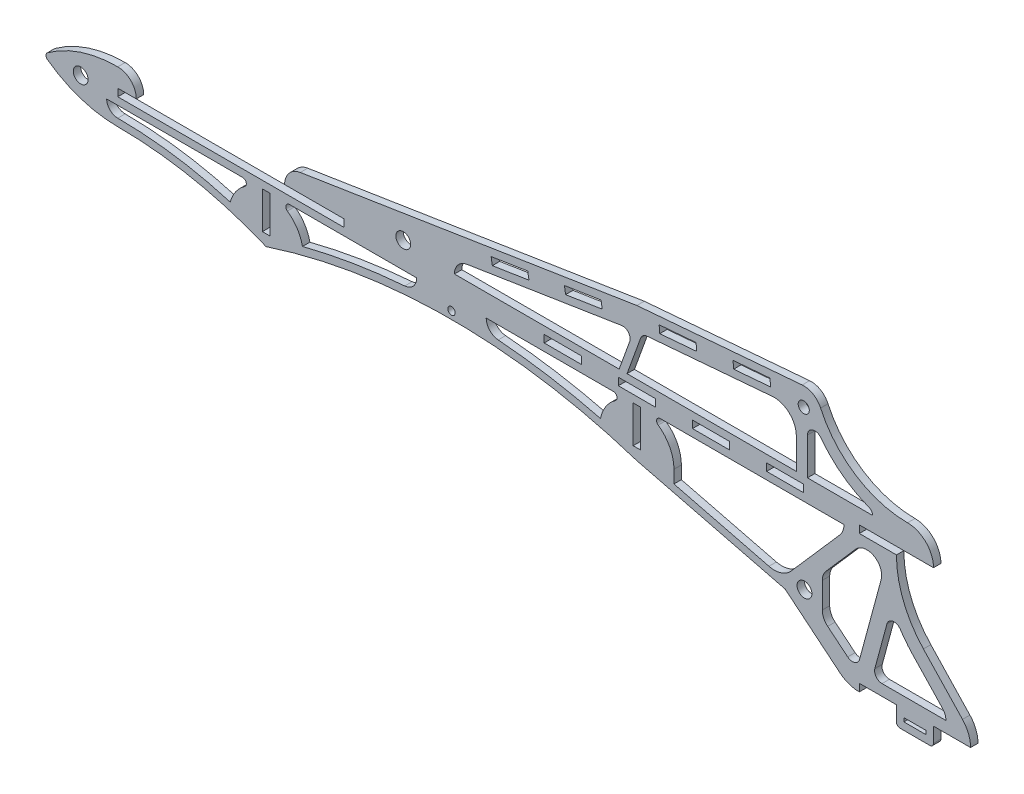
SolidWorks part; units mm, degrees
ref_plane "Front Plane" through (0, 0, 0) normal (0, 0, 1) x (1, 0, 0)
ref_plane "Top Plane" through (0, 0, 0) normal (0, 1, 0) x (1, 0, 0)
ref_plane "Right Plane" through (0, 0, 0) normal (1, 0, 0) x (0, 0, -1)
sketch "Sketch1" plane through (0, 0, 0) normal (0, 0, 1) x (1, 0, 0)
  line L0 (25, 2) -> (20, 2)
  line L1 (-10, 0) -> (249.25, 0) construction
  line L2 (20, 2) -> (20, 0)
  line L3 (20, 0) -> (81, 0)
  line L4 (65, 2) -> (81, 2)
  line L5 (81, 2) -> (81, 0)
  line L6 (66.3246, -2) -> (100.6353, -2)
  line L7 (59, -12) -> (59, -2)
  line L8 (61, -12) -> (59, -12)
  line L9 (59, -2) -> (61, -2)
  line L10 (17, -2) -> (53.6754, -2)
  line L11 (160, 21.25) -> (69.2214, 6.939)
  line L12 (160, 21.25) -> (204.5828, 24.9826)
  line L13 (160, -15) -> (200, -25)
  line L14 (200, -25) -> (214.7845, -37.1754)
  line L15 (219.8701, -39) -> (220, -39)
  line L16 (220, -39) -> (220, -37)
  line L17 (220, -37) -> (230, -37)
  line L18 (230, -37) -> (230, -41)
  line L19 (231, -42) -> (239, -42)
  line L20 (240, -41) -> (240, -37)
  line L21 (240, -37) -> (250, -37)
  line L22 (237.2765, -20.3267) -> (247.8212, -31.5124)
  line L23 (232, -39) -> (238, -39)
  line L24 (232, -39) -> (232, -40)
  line L25 (232, -40) -> (238, -40)
  line L26 (238, -39) -> (238, -40)
  line L27 (230, -2) -> (220, -2)
  line L29 (220, 0) -> (240, 0)
  line L30 (61, -2) -> (61, -12)
  line L31 (159, -12) -> (161, -12)
  line L32 (159, -12) -> (159, -2)
  line L33 (159, -2) -> (161, -2)
  line L34 (161, -12) -> (161, -2)
  line L35 (170, -15.4384) -> (195.6265, -21.8451)
  line L36 (119.3647, -2) -> (153.6754, -2)
  line L37 (166.3246, -2) -> (215.8581, -2)
  line L38 (170, -12) -> (170, -15.4384)
  line L39 (160.5551, -13.0772) -> (200.4851, -23.0597) construction
  line L40 (225.88, -9.8441) -> (220.0588, -31.3826)
  line L41 (155.22, 4) -> (158.0674, 11.8696)
  line L42 (162.7314, 15.4577) -> (196.4994, 18.2848)
  line L43 (155.8752, 14.5256) -> (114.1717, 7.9512)
  line L44 (157.3469, 4) -> (161.0176, 14.1451)
  line L45 (110.7946, 4) -> (155.22, 4)
  line L46 (160.7184, 15.2892) -> (70.1557, 1.0122) construction
  line L47 (157.1007, 3.3195) -> (161.0998, 14.3723) construction
  line L48 (157.3469, 4) -> (203, 4)
  line L49 (160.7184, 15.2892) -> (205.0834, 19.0035) construction
  line L50 (155.22, 4) -> (159.2191, 15.0528) construction
  line L51 (203, 12.3057) -> (203, 4)
  line L52 (206, 13.9815) -> (206, 4)
  line L53 (206, 4) -> (223.5862, 4)
  line L54 (166, 19.7453) -> (175.9651, 20.5796)
  line L55 (150.334, 17.7015) -> (140.456, 16.1442)
  line L56 (166.1669, 17.7523) -> (176.132, 18.5866)
  line L57 (150.6455, 15.7259) -> (140.7675, 14.1686)
  line L58 (121.0114, 11.0542) -> (120.7, 13.0298)
  line L59 (130.8895, 12.6114) -> (130.578, 14.587)
  line L60 (160.2395, 19.2631) -> (69.5328, 4.9634) construction
  line L61 (160.4789, 17.2761) -> (69.8443, 2.9878) construction
  line L62 (140.7675, 14.1686) -> (140.456, 16.1442)
  line L63 (150.6455, 15.7259) -> (150.334, 17.7015)
  line L64 (130.578, 14.587) -> (120.7, 13.0298)
  line L65 (130.8895, 12.6114) -> (121.0114, 11.0542)
  line L66 (166.1669, 17.7523) -> (166, 19.7453)
  line L67 (176.132, 18.5866) -> (175.9651, 20.5796)
  line L68 (160.4789, 17.2761) -> (204.9166, 20.9965) construction
  line L69 (160.2395, 19.2631) -> (204.7497, 22.9895) construction
  line L70 (186.0971, 19.4209) -> (185.9303, 21.4139)
  line L71 (196.0623, 20.2552) -> (195.8954, 22.2482)
  line L72 (185.9303, 21.4139) -> (195.8954, 22.2482)
  line L73 (186.0971, 19.4209) -> (196.0623, 20.2552)
  line L74 (220, -2) -> (220, 0)
  line L75 (227.4331, -19.4284) -> (224.1764, -31.4782)
  line L76 (234.3659, -23.0705) -> (242.4058, -31.5992)
  line L77 (231.8615, -3.0436) -> (221.9178, -39.8353) construction
  line L78 (226.1072, -34) -> (243.3591, -34)
  line L79 (228, -2) -> (218.0563, -38.7917) construction
  line L80 (210.9909, -15.3206) -> (219.0094, -6.165)
  line L81 (234.3659, -23.0705) -> (244.9106, -34.2562) construction
  line L82 (201.5953, -19.9773) -> (214.7434, -4.9648)
  line L83 (210, -17.956) -> (210, -24.8703)
  line L84 (202.1903, -25.3691) -> (220.3491, -4.6354) construction
  line L85 (199.1812, -22.7337) -> (217.34, -2) construction
  line L86 (211.4572, -27.958) -> (216.8566, -32.4046)
  line L87 (135, 0) -> (145, 0)
  line L88 (135, 0) -> (135, 2)
  line L89 (135, 2) -> (145, 2)
  line L90 (145, 0) -> (145, 2)
  line L91 (155, 0) -> (165, 0)
  line L92 (155, 0) -> (155, 2)
  line L93 (155, 2) -> (165, 2)
  line L94 (165, 0) -> (165, 2)
  line L95 (175, 0) -> (185, 0)
  line L96 (175, 0) -> (175, 2)
  line L97 (175, 2) -> (185, 2)
  line L98 (185, 0) -> (185, 2)
  line L99 (195, 0) -> (205, 0)
  line L100 (195, 0) -> (195, 2)
  line L101 (195, 2) -> (205, 2)
  line L102 (205, 0) -> (205, 2)
  arc A0 (1.0556, 0.8069) -> (20, 7) centre (20, -25.0714) cw
  arc A1 (1.0556, -0.8069) -> (20, -7) centre (20, 25.0714) ccw
  arc A2 (25, 2) -> (20, 7) centre (20, 2) ccw
  arc A3 (20, -7) -> (60, -15) centre (20, -111) cw
  circle A4 centre (10, 0) radius 2
  arc A5 (60, -15) -> (160, -15) centre (110, -167.25) cw
  arc A6 (69.2214, 6.939) -> (65, 2) centre (70, 2) ccw
  arc A7 (209.5487, 22.0758) -> (204.5828, 24.9826) centre (205, 20) ccw
  circle A8 centre (205, 20) radius 1.5
  arc A9 (250, -37) -> (247.8212, -31.5124) centre (242, -37) ccw
  arc A10 (239, -42) -> (240, -41) centre (239, -41) ccw
  arc A11 (230, -41) -> (231, -42) centre (231, -41) ccw
  arc A12 (214.7845, -37.1754) -> (219.8701, -39) centre (219.8701, -31) ccw
  arc A13 (230, -2) -> (237.2765, -20.3267) centre (256.7172, -2) ccw
  arc A14 (240, 0) -> (233, 7) centre (233, 0) ccw
  arc A15 (209.5487, 22.0758) -> (233, 7) centre (233, 32.7778) ccw
  circle A16 centre (110, -5.0031) radius 1
  arc A17 (54.2504, -3.8182) -> (50.335, -9.4333) centre (60, -12) ccw
  arc A18 (154.2504, -3.8182) -> (150.1907, -10.0566) centre (160, -12) ccw
  arc A19 (54.2504, -3.8182) -> (53.6754, -2) centre (53.6754, -3) ccw
  arc A20 (66.3246, -2) -> (65.7496, -3.8182) centre (66.3246, -3) ccw
  arc A21 (20, -5) -> (50.335, -9.4333) centre (20, -111) cw
  arc A22 (69.8093, -10.0566) -> (97.407, -5.4894) centre (110, -167.25) cw
  arc A23 (17, -2) -> (20, -5) centre (20, -2) ccw
  arc A24 (97.407, -5.4894) -> (100.6353, -2) centre (97.1353, -2) ccw
  arc A25 (20, -5) -> (60.0812, -12.87) centre (20, -111) cw construction
  arc A26 (69.8093, -10.0566) -> (65.7496, -3.8182) centre (60, -12) ccw
  circle A27 centre (97, 5) radius 2
  arc A28 (60.0812, -12.87) -> (160.5551, -13.0772) centre (110, -167.25) cw construction
  arc A29 (119.3647, -2) -> (122.593, -5.4894) centre (122.8647, -2) ccw
  arc A30 (122.593, -5.4894) -> (150.1907, -10.0566) centre (110, -167.25) cw
  arc A31 (154.2504, -3.8182) -> (153.6754, -2) centre (153.6754, -3) ccw
  arc A32 (170, -12) -> (165.7496, -3.8182) centre (160, -12) ccw
  arc A33 (166.3246, -2) -> (165.7496, -3.8182) centre (166.3246, -3) ccw
  arc A34 (114.1717, 7.9512) -> (110.7946, 4) centre (114.7946, 4) ccw
  arc A35 (1.0556, 0.8069) -> (1.0556, -0.8069) centre (1.6463, 0) ccw
  arc A36 (161.0176, 14.1451) -> (162.7314, 15.4577) centre (162.8983, 13.4647) cw
  arc A37 (158.0674, 11.8696) -> (155.8752, 14.5256) centre (156.1867, 12.55) ccw
  arc A38 (196.4994, 18.2848) -> (203, 12.3057) centre (197, 12.3057) cw
  arc A39 (209.5986, 15.1834) -> (222.6181, 5.4025) centre (233, 32.7778) ccw
  arc A40 (209.5986, 15.1834) -> (206, 13.9815) centre (208, 13.9815) ccw
  arc A41 (223.5862, 4) -> (222.6181, 5.4025) centre (222.0862, 4) ccw
  arc A42 (206.3646, 20.6227) -> (233, 3.5) centre (233, 32.7778) ccw construction
  circle A43 centre (205.2, -22.5) radius 2
  arc A44 (231.036, -18.8529) -> (234.3659, -23.0705) centre (256.7172, -2) ccw
  arc A45 (227.4331, -19.4284) -> (231.036, -18.8529) centre (229.3639, -19.9502) cw
  arc A46 (226, -2) -> (234.3659, -23.0705) centre (256.7172, -2) ccw construction
  arc A47 (224.1764, -31.4782) -> (226.1072, -34) centre (226.1072, -32) ccw
  arc A48 (243.3591, -34) -> (242.4058, -31.5992) centre (239.8591, -34) ccw
  arc A49 (225.88, -9.8441) -> (219.0094, -6.165) centre (222.0185, -8.8004) ccw
  arc A50 (220.0588, -31.3826) -> (216.8566, -32.4046) centre (218.128, -30.8608) cw
  arc A51 (210.9909, -15.3206) -> (210, -17.956) centre (214, -17.956) ccw
  arc A52 (211.4572, -27.958) -> (210, -24.8703) centre (214, -24.8703) cw
  arc A53 (214.7434, -4.9648) -> (215.8581, -2) centre (211.3581, -2) ccw
  arc A54 (201.5953, -19.9773) -> (195.6265, -21.8451) centre (197.0817, -16.0242) cw
  point P32 (200, -25)
  point P46 (230, -2)
  point P62 (110, -7)
  point P116 (0, 0)
  dimension "D1" = 1
  dimension "D2" = 8
  dimension "D3" = 10
  dimension "D4" = 10
  dimension "D5" = 2
  dimension "D6" = 2
  dimension "D8" = 3.5
  dimension "D9" = 3.5
  dimension "D10" = 2
  dimension "D11" = 2
  dimension "D12" = 4
  dimension "D13" = 3
  dimension "D15" = 4
  dimension "D16" = 1
  dimension "D18" = 2
  dimension "D19" = 6
  dimension "D21" = 4
  dimension "D22" = 3
  dimension "D33" = 4
  dimension "D36" = 2
  dimension "D37" = 7
  dimension "D39" = 8
  dimension "D40" = 2
  dimension "D41" = 4
  dimension "D42" = 9
  dimension "D43" = 6
  dimension "D25" = 120.7
  dimension "D26" = 10
  dimension "D27" = 10
  dimension "D28" = 10
  dimension "D29" = 166
  dimension "D30" = 10
  dimension "D31" = 10
  dimension "D32" = 10
  dimension "D44" = 135
  dimension "D45" = 10
  dimension "D46" = 220
  dimension "D7" = 2
  dimension "D14" = 6
  dimension "D17" = 2
  dimension "D20" = 3.5
  dimension "D23" = 2
  dimension "D24" = 4
  dimension "D34" = 4
  dimension "D35" = 4
  dimension "D38" = 4
extrude "Boss-Extrude1" add sketch "Sketch1" along normal blind 2
